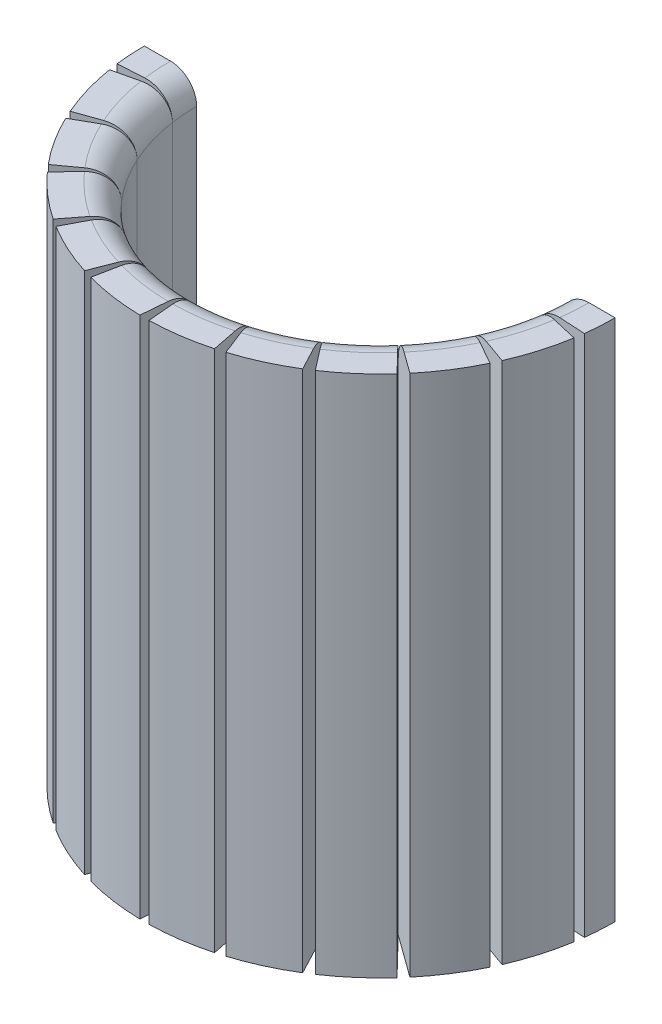
SolidWorks part; units mm, degrees
material "PTFE (general)"
ref_plane "Front Plane" through (0, 0, 0) normal (0, 0, 1) x (1, 0, 0)
ref_plane "Top Plane" through (0, 0, 0) normal (0, 1, 0) x (1, 0, 0)
ref_plane "Right Plane" through (0, 0, 0) normal (1, 0, 0) x (0, 0, -1)
sketch "Sketch1" plane through (0, 0, 0) normal (0, 1, 0) x (1, 0, 0)
  line L1 (90, 0) -> (70, 0)
  line L2 (-90, 0) -> (-70, 0)
  arc A0 (-90, 0) -> (90, 0) centre (0, 0) ccw
  arc A1 (-70, 0) -> (70, 0) centre (0, 0) ccw
  dimension "D1" = 90
  dimension "D2" = 70
extrude "Boss-Extrude1" add sketch "Sketch1" along normal blind 200
fillet "Fillet1" radius 10 1 edges at (0, 200, 70)
sketch "Sketch2" plane through (0, 0, 0) normal (0, -1, 0) x (1, 0, 0)
  line L0 (0, 70) -> (-1.7483, 89.983)
  line L1 (0, 70) -> (1.7483, 89.983)
  line L2 (19.7213, 67.1645) -> (23.6737, 86.8306)
  line L3 (19.7213, 67.1645) -> (27.0286, 85.8455)
  line L4 (37.8449, 58.8877) -> (47.1777, 76.6437)
  line L5 (37.8449, 58.8877) -> (50.1192, 74.7533)
  line L6 (52.9025, 45.8403) -> (66.8597, 60.2476)
  line L7 (52.9025, 45.8403) -> (69.1495, 57.6051)
  line L8 (63.6742, 29.0791) -> (81.1252, 38.9706)
  line L9 (63.6742, 29.0791) -> (82.5777, 35.79)
  line L10 (69.2875, 9.962) -> (88.8183, 14.5364)
  line L11 (69.2875, 9.962) -> (89.3159, 11.0754)
  line L12 (69.2875, -9.962) -> (89.3159, -11.0754)
  line L13 (69.2875, -9.962) -> (88.8183, -14.5364)
  line L14 (63.6742, -29.0791) -> (82.5777, -35.79)
  line L15 (63.6742, -29.0791) -> (81.1252, -38.9706)
  line L16 (52.9025, -45.8403) -> (69.1495, -57.6051)
  line L17 (52.9025, -45.8403) -> (66.8597, -60.2476)
  line L18 (37.8449, -58.8877) -> (50.1192, -74.7533)
  line L19 (37.8449, -58.8877) -> (47.1777, -76.6437)
  line L20 (19.7213, -67.1645) -> (27.0286, -85.8455)
  line L21 (19.7213, -67.1645) -> (23.6737, -86.8306)
  line L22 (0, -70) -> (1.7483, -89.983)
  line L23 (0, -70) -> (-1.7483, -89.983)
  line L24 (-19.7213, -67.1645) -> (-23.6737, -86.8306)
  line L25 (-19.7213, -67.1645) -> (-27.0286, -85.8455)
  line L26 (-37.8449, -58.8877) -> (-47.1777, -76.6437)
  line L27 (-37.8449, -58.8877) -> (-50.1192, -74.7533)
  line L28 (-52.9025, -45.8403) -> (-66.8597, -60.2476)
  line L29 (-52.9025, -45.8403) -> (-69.1495, -57.6051)
  line L30 (-63.6742, -29.0791) -> (-81.1252, -38.9706)
  line L31 (-63.6742, -29.0791) -> (-82.5777, -35.79)
  line L32 (-69.2875, -9.962) -> (-88.8183, -14.5364)
  line L33 (-69.2875, -9.962) -> (-89.3159, -11.0754)
  line L34 (-69.2875, 9.962) -> (-89.3159, 11.0754)
  line L35 (-69.2875, 9.962) -> (-88.8183, 14.5364)
  line L36 (-63.6742, 29.0791) -> (-82.5777, 35.79)
  line L37 (-63.6742, 29.0791) -> (-81.1252, 38.9706)
  line L38 (-52.9025, 45.8403) -> (-69.1495, 57.6051)
  line L39 (-52.9025, 45.8403) -> (-66.8597, 60.2476)
  line L40 (-37.8449, 58.8877) -> (-50.1192, 74.7533)
  line L41 (-37.8449, 58.8877) -> (-47.1777, 76.6437)
  line L42 (-19.7213, 67.1645) -> (-27.0286, 85.8455)
  line L43 (-19.7213, 67.1645) -> (-23.6737, 86.8306)
  arc A0 (27.0286, 85.8455) -> (23.6737, 86.8306) centre (0, 0) ccw
  arc A1 (50.1192, 74.7533) -> (47.1777, 76.6437) centre (0, 0) ccw
  arc A2 (70, 0) -> (-70, 0) centre (0, 0) ccw construction
  arc A3 (90, 0) -> (-90, 0) centre (0, 0) ccw construction
  arc A4 (1.7483, 89.983) -> (-1.7483, 89.983) centre (0, 0) ccw
  arc A5 (69.1495, 57.6051) -> (66.8597, 60.2476) centre (0, 0) ccw
  arc A6 (82.5777, 35.79) -> (81.1252, 38.9706) centre (0, 0) ccw
  arc A7 (89.3159, 11.0754) -> (88.8183, 14.5364) centre (0, 0) ccw
  arc A8 (88.8183, -14.5364) -> (89.3159, -11.0754) centre (0, 0) ccw
  arc A9 (81.1252, -38.9706) -> (82.5777, -35.79) centre (0, 0) ccw
  arc A10 (66.8597, -60.2476) -> (69.1495, -57.6051) centre (0, 0) ccw
  arc A11 (47.1777, -76.6437) -> (50.1192, -74.7533) centre (0, 0) ccw
  arc A12 (23.6737, -86.8306) -> (27.0286, -85.8455) centre (0, 0) ccw
  arc A13 (-1.7483, -89.983) -> (1.7483, -89.983) centre (0, 0) ccw
  arc A14 (-27.0286, -85.8455) -> (-23.6737, -86.8306) centre (0, 0) ccw
  arc A15 (-50.1192, -74.7533) -> (-47.1777, -76.6437) centre (0, 0) ccw
  arc A16 (-69.1495, -57.6051) -> (-66.8597, -60.2476) centre (0, 0) ccw
  arc A17 (-82.5777, -35.79) -> (-81.1252, -38.9706) centre (0, 0) ccw
  arc A18 (-89.3159, -11.0754) -> (-88.8183, -14.5364) centre (0, 0) ccw
  arc A19 (-88.8183, 14.5364) -> (-89.3159, 11.0754) centre (0, 0) ccw
  arc A20 (-81.1252, 38.9706) -> (-82.5777, 35.79) centre (0, 0) ccw
  arc A21 (-66.8597, 60.2476) -> (-69.1495, 57.6051) centre (0, 0) ccw
  arc A22 (-47.1777, 76.6437) -> (-50.1192, 74.7533) centre (0, 0) ccw
  arc A23 (-23.6737, 86.8306) -> (-27.0286, 85.8455) centre (0, 0) ccw
  point P8 (0, 90)
  point P77 (0, 0)
  dimension "D1" = 90
  dimension "D2" = 10
  dimension "D3" = 22
extrude "Cut-Extrude1" cut sketch "Sketch2" against normal up to surface (200 mm away)
